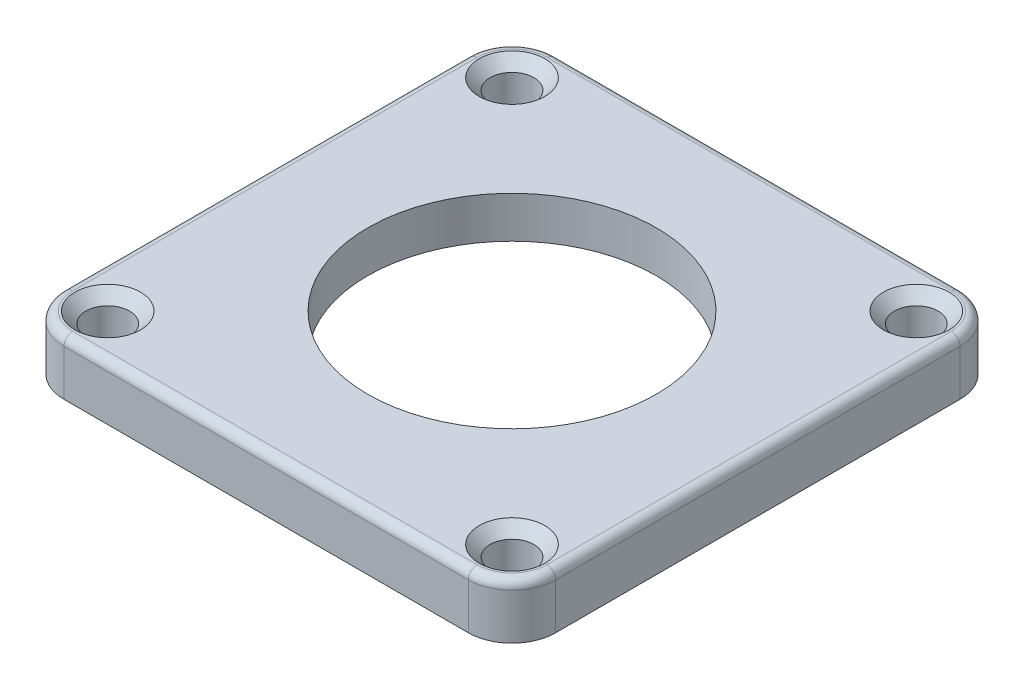
SolidWorks part; units mm, degrees
material "PBT General Purpose"
ref_plane "Front Plane" through (0, 0, 0) normal (0, 0, 1) x (1, 0, 0)
ref_plane "Top Plane" through (0, 0, 0) normal (0, 1, 0) x (1, 0, 0)
ref_plane "Right Plane" through (0, 0, 0) normal (1, 0, 0) x (0, 0, -1)
sketch "Sketch1" plane through (0, 0, 0) normal (0, 1, 0) x (1, 0, 0)
  line L1 (-28.575, -28.575) -> (28.575, -28.575)
  line L2 (-28.575, -28.575) -> (-28.575, 28.575)
  line L3 (-28.575, 28.575) -> (28.575, 28.575)
  line L4 (28.575, -28.575) -> (28.575, 28.575)
  line L5 (-28.575, -28.575) -> (28.575, 28.575) construction
  line L6 (-28.575, 28.575) -> (28.575, -28.575) construction
  point P0 (0, 0)
  dimension "D1" = 57.15
extrude "Boss-Extrude2" add sketch "Sketch1" along normal blind 6.35
fillet "Fillet1" radius 5.08 4 edges at (-28.575, 3.175, 28.575) (28.575, 3.175, 28.575) (28.575, 3.175, -28.575) (-28.575, 3.175, -28.575)
sketch "Sketch2" plane through (0, 0, 0) normal (0, -1, 0) x (1, 0, 0)
  circle A0 centre (0, 0) radius 19.05
  dimension "D1" = 38.1
extrude "Cut-Extrude1" cut sketch "Sketch2" against normal blind 1.524
hole_wizard "CSK for #1 Flat Head Machine Screw (100)2" positions "Sketch13" profile "Sketch12" countersink size "#1" standard "ANSI Inch" end condition through all
sketch "Sketch13" plane through (0, 6.35, 0) normal (0, 1, 0) x (1, 0, 0)
  point P0 (-23.495, 23.495)
  point P3 (23.495, 23.495)
  point P6 (-23.495, -23.495)
  point P9 (23.495, -23.495)
sketch "Sketch12" plane through (-23.495, 6.35, -23.495) normal (1, 0, 0) x (0, 0, 1)
  line L0 (0, 0) -> (0, 6.35)
  line L1 (0, 6.35) -> (2.54, 6.35)
  line L2 (2.54, 6.35) -> (2.54, 1.27)
  line L3 (2.54, 1.27) -> (3.81, 0)
  line L5 (3.81, 0) -> (0, 0)
  line L6 (-2.54, 1.27) -> (-3.81, 0) construction
  line L11 (0, -6.35) -> (0, 107.95) construction
  dimension "Thru Hole Dia." = 5.08
  dimension "Thru Hole Depth" = 6.35
  dimension "Near C'Sink Dia." = 7.62
  dimension "Near C'Sink Angle" = 90
sketch "Sketch14" plane through (0, 6.35, 0) normal (0, 1, 0) x (1, 0, 0)
  circle A0 centre (0, 0) radius 3.175
extrude "Cut-Extrude2" cut sketch "Sketch14" against normal up to surface (4.826 mm away) up to face at (0, 1.524, -19.05)
fillet "Fillet2" radius 1.016 8 edges at (-27.0871, 6.35, -27.0871) (0, 6.35, -28.575) (27.0871, 6.35, -27.0871) (28.575, 6.35, 0) (27.0871, 6.35, 27.0871) (0, 6.35, 28.575) (-27.0871, 6.35, 27.0871) (-28.575, 6.35, 0)
sketch "Sketch15" plane through (0, 6.35, 0) normal (0, 1, 0) x (1, 0, 0)
  circle A0 centre (0, 0) radius 16.764
extrude "Cut-Extrude4" cut sketch "Sketch15" against normal up to surface (4.826 mm away) contours A0 up to face at (0, 1.524, -3.175)
